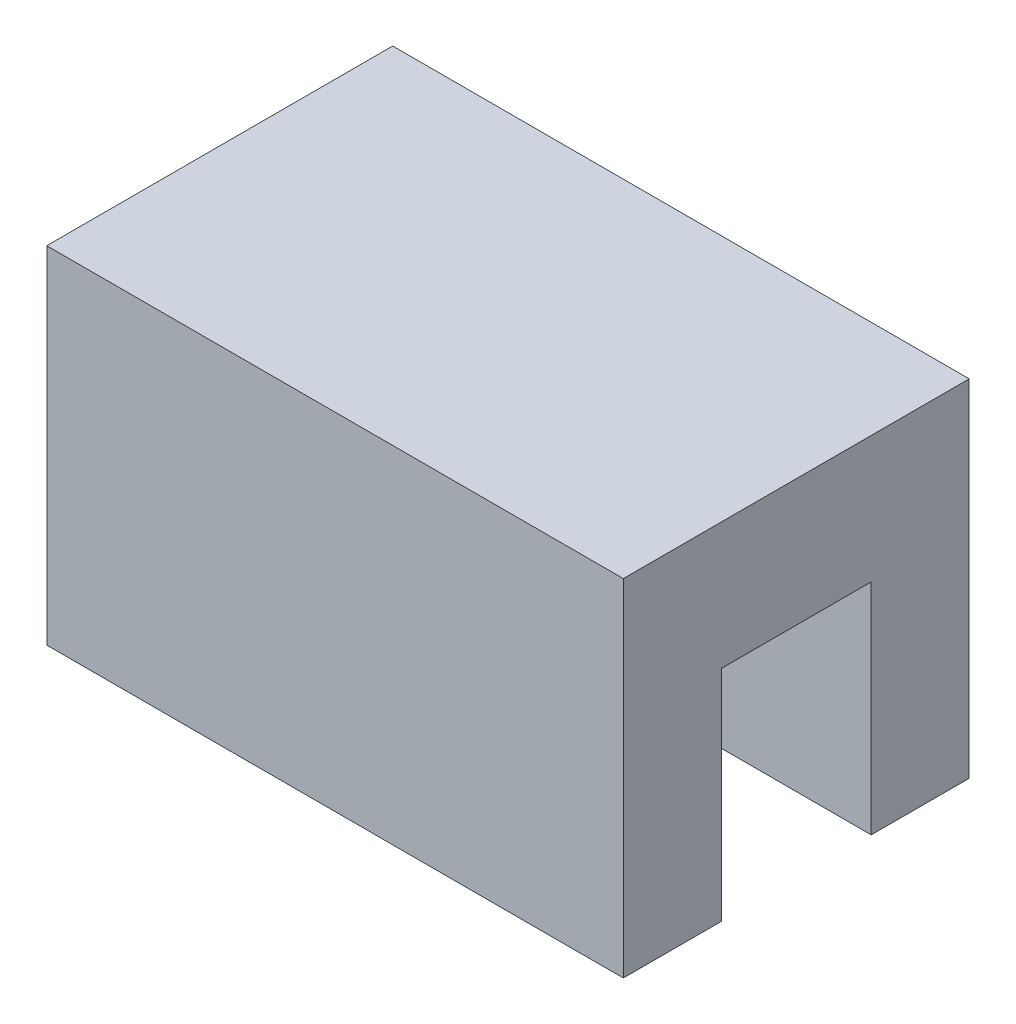
SolidWorks part; units mm, degrees
ref_plane "Front Plane" through (0, 0, 0) normal (0, 0, 1) x (1, 0, 0)
ref_plane "Top Plane" through (0, 0, 0) normal (0, 1, 0) x (1, 0, 0)
ref_plane "Right Plane" through (0, 0, 0) normal (1, 0, 0) x (0, 0, -1)
sketch "Sketch1" plane through (0, 0, 0) normal (1, 0, 0) x (0, 0, -1)
  line L1 (0, 0) -> (30, 0)
  line L2 (0, 0) -> (0, 30)
  line L3 (0, 30) -> (30, 30)
  line L4 (30, 0) -> (30, 30)
  dimension "D1" = 30
  dimension "D2" = 30
extrude "Boss-Extrude1" add sketch "Sketch1" along normal blind 50
sketch "Sketch2" plane through (50, 0, 0) normal (1, 0, 0) x (0, 0, -1)
  line L0 (15, 0) -> (15, 30) construction
  line L1 (0, 0) -> (30, 0) construction
  line L2 (30, 30) -> (0, 30) construction
  line L4 (8.5, 19) -> (21.5, 19)
  line L5 (8.5, 19) -> (8.5, 0)
  line L6 (8.5, 0) -> (21.5, 0)
  line L7 (21.5, 19) -> (21.5, 0)
  dimension "D1" = 13
  dimension "D2" = 19
  dimension "D3" = 6.5
  dimension "D4" = 0
extrude "Cut-Extrude1" cut sketch "Sketch2" against normal blind 18
